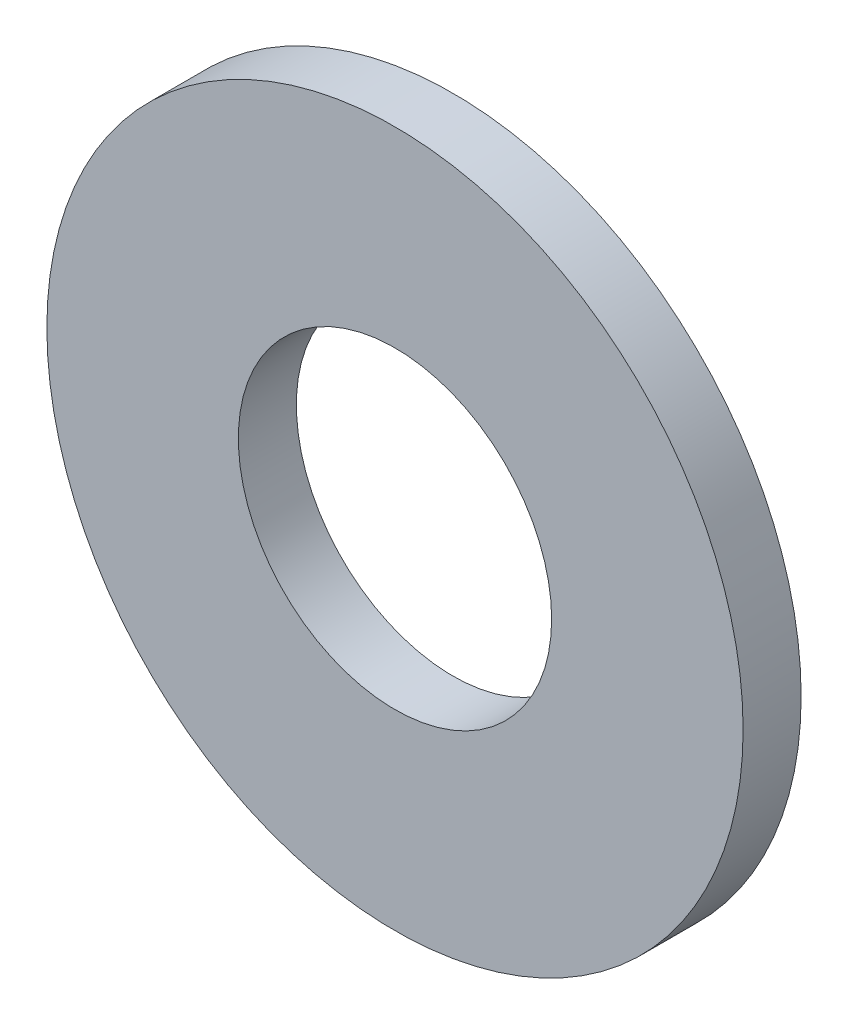
SolidWorks part; units mm, degrees
ref_plane "Front Plane" through (0, 0, 0) normal (0, 0, 1) x (1, 0, 0)
ref_plane "Top Plane" through (0, 0, 0) normal (0, 1, 0) x (1, 0, 0)
ref_plane "Right Plane" through (0, 0, 0) normal (1, 0, 0) x (0, 0, -1)
sketch "Sketch1" plane through (0, 0, 0) normal (0, 0, 1) x (1, 0, 0)
  circle A0 centre (0, 0) radius 3
  circle A1 centre (0, 0) radius 1.35
extrude "Washer_Envelope" add sketch "Sketch1" along normal blind 0.5
